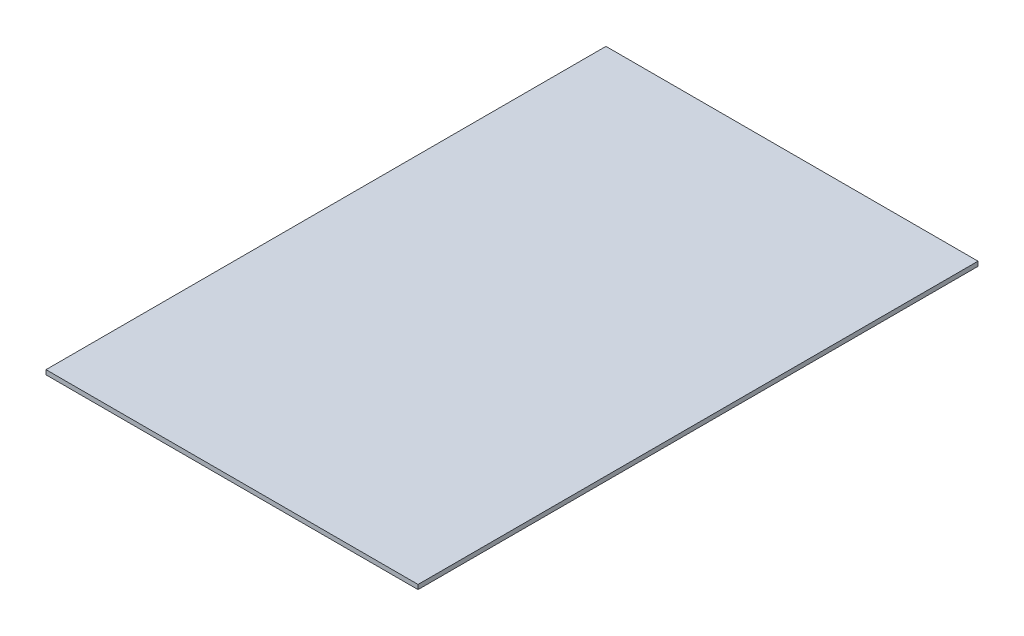
SolidWorks part; units mm, degrees
ref_plane "Front Plane" through (0, 0, 0) normal (0, 0, 1) x (1, 0, 0)
ref_plane "Top Plane" through (0, 0, 0) normal (0, 1, 0) x (1, 0, 0)
ref_plane "Right Plane" through (0, 0, 0) normal (1, 0, 0) x (0, 0, -1)
sketch "Sketch1" plane through (0, 0, 0) normal (0, 1, 0) x (1, 0, 0)
  line L1 (-99, 149) -> (99, 149)
  line L2 (-99, 149) -> (-99, -149)
  line L3 (-99, -149) -> (99, -149)
  line L4 (99, 149) -> (99, -149)
  line L5 (-99, 149) -> (99, -149) construction
  line L6 (-99, -149) -> (99, 149) construction
  point P0 (0, 0)
  dimension "D1" = 298
  dimension "D2" = 198
extrude "Boss-Extrude1" add sketch "Sketch1" along normal blind 2.4
